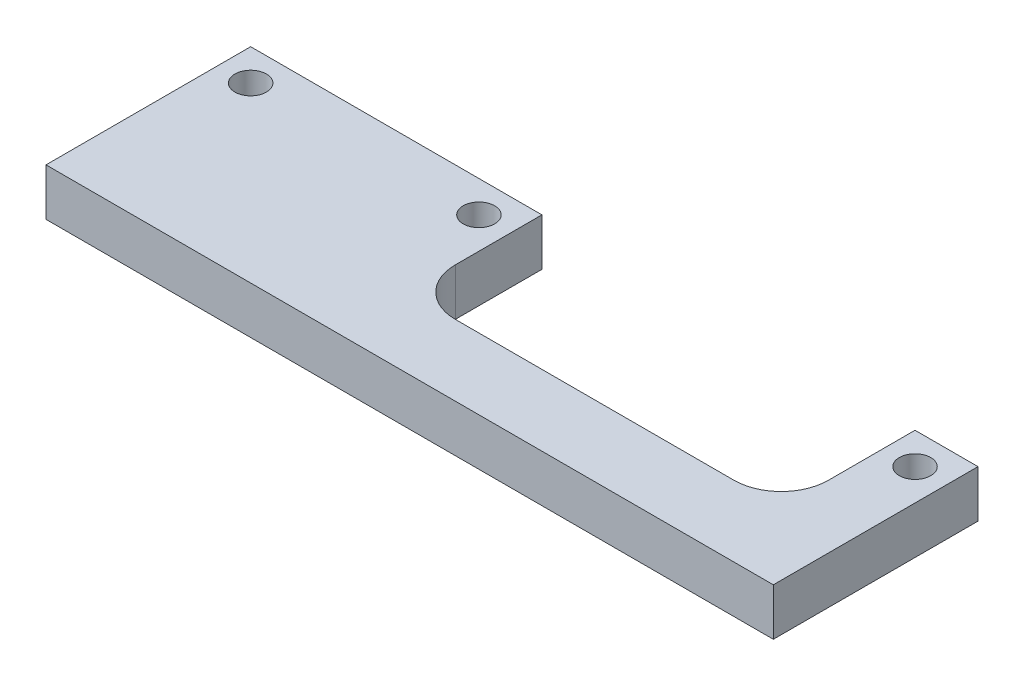
SolidWorks part; units mm, degrees
ref_plane "Front Plane" through (0, 0, 0) normal (0, 0, 1) x (1, 0, 0)
ref_plane "Top Plane" through (0, 0, 0) normal (0, 1, 0) x (1, 0, 0)
ref_plane "Right Plane" through (0, 0, 0) normal (1, 0, 0) x (0, 0, -1)
sketch "Sketch1" plane through (0, 0, 0) normal (0, 1, 0) x (1, 0, 0)
  line L1 (-23.1, -6.5) -> (23.1, -6.5)
  line L2 (-23.1, -6.5) -> (-23.1, 6.5)
  line L3 (-23.1, 6.5) -> (23.1, 6.5)
  line L4 (23.1, -6.5) -> (23.1, 6.5)
  line L5 (-23.1, -6.5) -> (23.1, 6.5) construction
  line L6 (-23.1, 6.5) -> (23.1, -6.5) construction
  point P0 (0, 0)
  dimension "D1" = 46.2
  dimension "D2" = 13
extrude "Boss-Extrude1" add sketch "Sketch1" along normal mid plane 3
sketch "Sketch3" plane through (0, 1.5, 0) normal (0, 1, 0) x (1, 0, 0)
  line L0 (23.1, 6.5) -> (-23.1, 6.5) construction
  line L1 (-23.1, 6.5) -> (-23.1, -6.5) construction
  line L2 (23.1, -6.5) -> (23.1, 6.5) construction
  circle A0 centre (-21.1, 4.5) radius 1
  circle A1 centre (-6.6, 4.5) radius 1
  circle A2 centre (21.1, 4.5) radius 1
  point P10 (0, 0)
  point P11 (0, 0)
  point P14 (0, 0)
  dimension "D1" = 2
  dimension "D3" = 2
  dimension "D2" = 2
  dimension "D4" = 14.5
  dimension "D5" = 2
extrude "Cut-Extrude1" cut sketch "Sketch3" against normal through all
sketch "Sketch4" plane through (0, 1.5, 0) normal (0, 1, 0) x (1, 0, 0)
  line L0 (23.1, 6.5) -> (-23.1, 6.5) construction
  line L1 (-4.6, 6.5) -> (19.1, 6.5)
  line L2 (-4.6, 6.5) -> (-4.6, -2)
  line L3 (-4.6, -2) -> (19.1, -2)
  line L4 (19.1, 6.5) -> (19.1, -2)
  line L5 (-23.1, 6.5) -> (-23.1, -6.5) construction
  line L6 (23.1, -6.5) -> (23.1, 6.5) construction
  line L7 (-23.1, -6.5) -> (23.1, -6.5) construction
  dimension "D1" = 18.5
  dimension "D2" = 4
  dimension "D3" = 4.5
extrude "Cut-Extrude2" cut sketch "Sketch4" against normal through all
fillet "Fillet1" radius 3 2 edges at (19.1, 0, 2) (-4.6, 0, 2)
